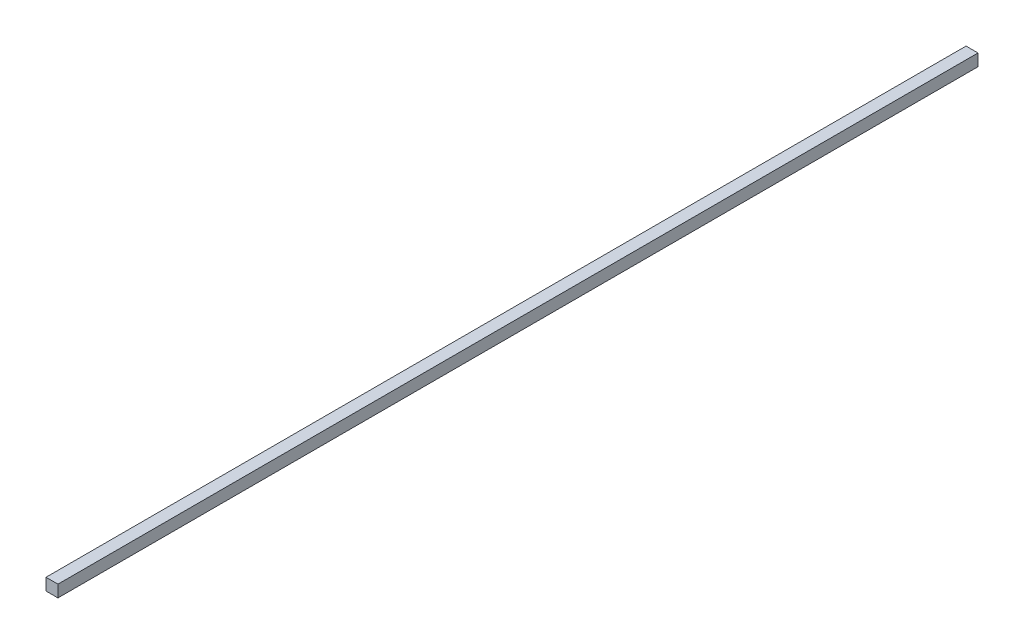
SolidWorks part; units mm, degrees
ref_plane "Front Plane" through (0, 0, 0) normal (0, 0, 1) x (1, 0, 0)
ref_plane "Top Plane" through (0, 0, 0) normal (0, 1, 0) x (1, 0, 0)
ref_plane "Right Plane" through (0, 0, 0) normal (1, 0, 0) x (0, 0, -1)
sketch "Sketch1" plane through (0, 0, 0) normal (0, 0, 1) x (1, 0, 0)
  line L1 (-43.25, 14.25) -> (-33.25, 14.25)
  line L2 (-43.25, 14.25) -> (-43.25, 4.25)
  line L3 (-43.25, 4.25) -> (-33.25, 4.25)
  line L4 (-33.25, 14.25) -> (-33.25, 4.25)
  dimension "D1" = 10
  dimension "D2" = 10
extrude "Boss-Extrude1" add sketch "Sketch1" along normal blind 770
